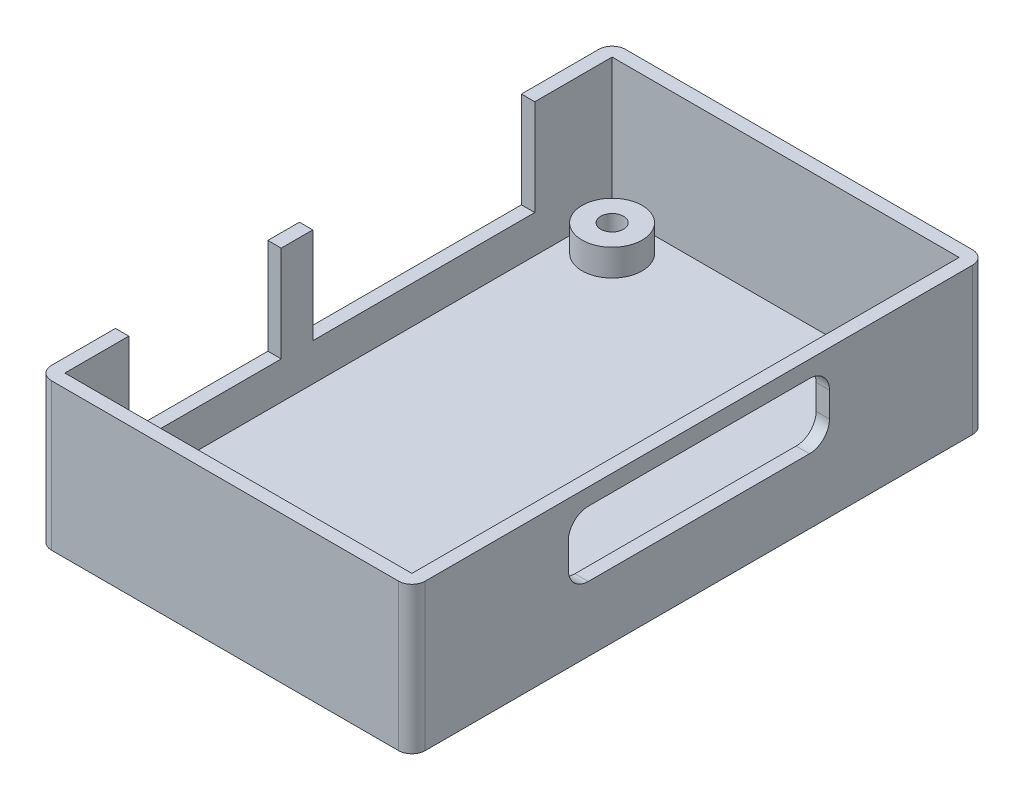
SolidWorks part; units mm, degrees
ref_plane "Ebene vorne" through (0, 0, 0) normal (0, 0, 1) x (1, 0, 0)
ref_plane "Ebene oben" through (0, 0, 0) normal (0, 1, 0) x (1, 0, 0)
ref_plane "Ebene rechts" through (0, 0, 0) normal (1, 0, 0) x (0, 0, -1)
sketch "Skizze1" plane through (0, 0, 0) normal (0, 1, 0) x (1, 0, 0)
  line L1 (0, 0) -> (56, 0)
  line L2 (0, 0) -> (0, 86)
  line L3 (0, 86) -> (56, 86)
  line L4 (56, 0) -> (56, 86)
  dimension "D1" = 56
  dimension "D2" = 86
extrude "Aufsatz-Linear austragen1" add sketch "Skizze1" along normal blind 22
shell "Wandung1" thickness 2
sketch "Skizze2" plane through (0, 2, 0) normal (0, 1, 0) x (1, 0, 0)
  line L1 (7.5, 7.5) -> (48.5, 7.5) construction
  line L2 (7.5, 7.5) -> (7.5, 78.5) construction
  line L3 (7.5, 78.5) -> (48.5, 78.5) construction
  line L4 (48.5, 7.5) -> (48.5, 78.5) construction
  line L6 (2, 84) -> (2, 2) construction
  line L7 (2, 2) -> (54, 2) construction
  circle A0 centre (7.5, 7.5) radius 4.5
  circle A1 centre (48.5, 7.5) radius 4.5
  circle A2 centre (48.5, 78.5) radius 4.5
  circle A3 centre (7.5, 78.5) radius 4.5
  dimension "D5" = 9
  dimension "D1" = 71
  dimension "D2" = 41
  dimension "D3" = 5.5
  dimension "D4" = 5.5
  dimension "D6" = 2
  dimension "D7" = 2
extrude "Aufsatz-Linear austragen2" add sketch "Skizze2" along normal blind 4
fillet "Verrundung1" radius 2 4 edges at (0, 11, -86) (56, 11, -86) (56, 11, 0) (0, 11, 0)
sketch "Skizze3" plane through (0, 0, 0) normal (-1, 0, 0) x (0, 0, 1)
  line L0 (0, 22) -> (0, 0) construction
  line L1 (-34.42, 22) -> (-11.58, 22)
  line L2 (-34.42, 22) -> (-34.42, 7.62)
  line L3 (-34.42, 7.62) -> (-11.58, 7.62)
  line L4 (-11.58, 22) -> (-11.58, 7.62)
  line L5 (-84, 22) -> (-2, 22) construction
  dimension "D1" = 11.58
  dimension "D2" = 22.84
  dimension "D3" = 14.38
extrude "Schnitt-Linear austragen1" cut sketch "Skizze3" against normal blind 2
hole_wizard "Stirnsenkung für M3 Zylinderschraube mit Innensechskant1" positions "Skizze5" profile "Skizze6" counterbore size "M3" standard "DIN"
sketch "Skizze5" plane through (0, 0, 0) normal (0, -1, 0) x (-1, 0, 0)
  line L1 (-48.5, 7.5) -> (-7.5, 7.5) construction
  line L2 (-48.5, 7.5) -> (-48.5, 78.5) construction
  line L3 (-48.5, 78.5) -> (-7.5, 78.5) construction
  line L4 (-7.5, 7.5) -> (-7.5, 78.5) construction
  line L5 (-2, 0) -> (-54, 0) construction
  line L6 (-56, 2) -> (-56, 84) construction
  point P0 (-48.5, 7.5)
  point P1 (-7.5, 78.5)
  point P100 (-48.5, 78.5)
  point P101 (-7.5, 7.5)
  dimension "D1" = 41
  dimension "D2" = 71
  dimension "D3" = 7.5
  dimension "D4" = 7.5
sketch "Skizze6" plane through (48.5, 0, -7.5) normal (1, 0, 0) x (0, 0, -1)
  line L0 (0, 0) -> (0, 15.0215)
  line L1 (0, 15.0215) -> (1.7, 14)
  line L2 (1.7, 14) -> (1.7, 3.4)
  line L3 (1.7, 3.4) -> (3.25, 3.4)
  line L5 (3.25, 3.4) -> (3.25, 0.025)
  line L6 (3.25, 0.025) -> (3.275, 0)
  line L7 (3.275, 0) -> (0, 0)
  line L8 (-3.25, 0.025) -> (-3.275, 0) construction
  line L10 (0, 15.0215) -> (-1.7, 14) construction
  line L11 (0, -6.35) -> (0, 107.95) construction
  dimension "Bohrerdurchmesser" = 3.4
  dimension "Bohrungstiefe" = 14
  dimension "Senkdurchmesser2" = 6.5
  dimension "Senktiefe2" = 3.4
  dimension "Senkdurchmesser4 (Oben)" = 6.55
  dimension "Senkwinkel2 (Oben)" = 90
  dimension "Spitzenwinkel" = 118
sketch "Skizze7" plane through (0, 0, 0) normal (-1, 0, 0) x (0, 0, 1)
  line L0 (0, 22) -> (0, 0) construction
  line L1 (-72.41, 7.62) -> (-39.15, 7.62)
  line L2 (-72.41, 7.62) -> (-72.41, 22)
  line L3 (-72.41, 22) -> (-39.15, 22)
  line L4 (-39.15, 7.62) -> (-39.15, 22)
  line L5 (-84, 22) -> (-34.42, 22) construction
  dimension "D1" = 39.15
  dimension "D2" = 33.26
  dimension "D3" = 14.38
extrude "Schnitt-Linear austragen2" cut sketch "Skizze7" against normal blind 10
sketch "Skizze8" plane through (56, 0, 0) normal (1, 0, 0) x (0, 0, -1)
  line L0 (0, 0) -> (0, 22) construction
  line L1 (23.43, 9.74) -> (62.57, 9.74)
  line L2 (23.43, 9.74) -> (23.43, 19.5)
  line L3 (23.43, 19.5) -> (62.57, 19.5)
  line L4 (62.57, 9.74) -> (62.57, 19.5)
  line L5 (2, 22) -> (84, 22) construction
  dimension "D1" = 23.43
  dimension "D2" = 39.14
  dimension "D3" = 12.26
  dimension "D4" = 2.5
extrude "Schnitt-Linear austragen3" cut sketch "Skizze8" against normal blind 10
fillet "Verrundung2" radius 3 4 edges at (55, 9.74, -23.43) (55, 9.74, -62.57) (55, 19.5, -62.57) (55, 19.5, -23.43)
